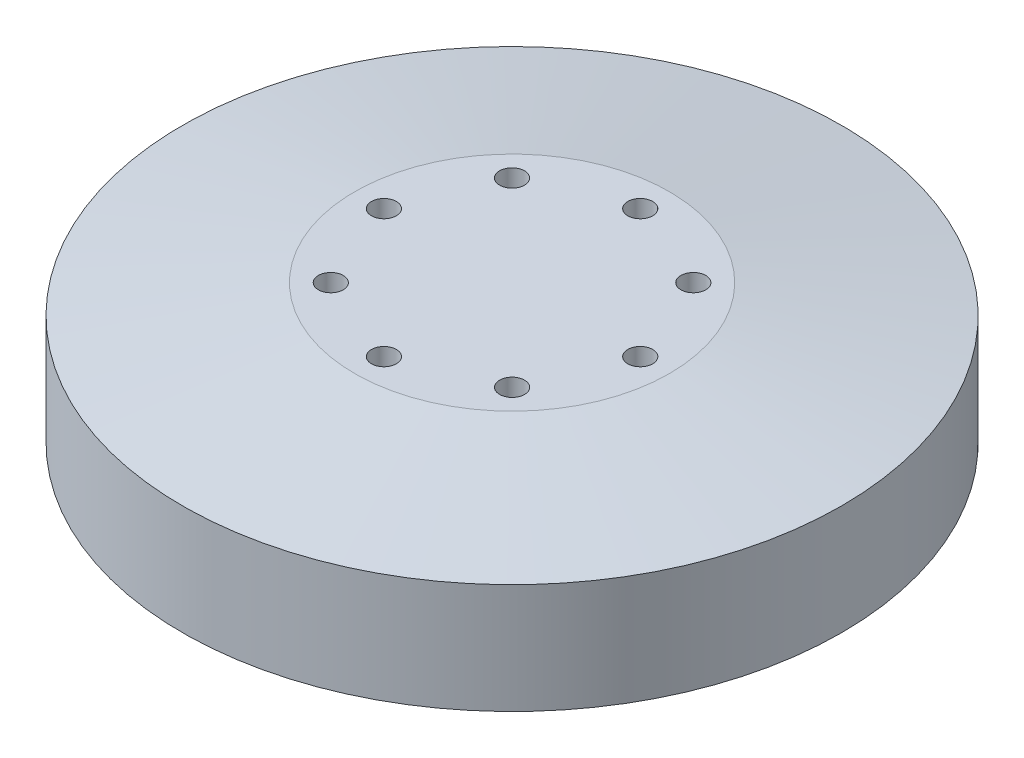
SolidWorks part; units mm, degrees
ref_plane "Front Plane" through (0, 0, 0) normal (0, 0, 1) x (1, 0, 0)
ref_plane "Top Plane" through (0, 0, 0) normal (0, 1, 0) x (1, 0, 0)
ref_plane "Right Plane" through (0, 0, 0) normal (1, 0, 0) x (0, 0, -1)
sketch "Sketch1" plane through (0, 0, 0) normal (0, 0, 1) x (1, 0, 0)
  line L0 (0, -9.45) -> (0, 9.45)
  line L1 (0, 9.45) -> (-21.5, 9.45)
  line L2 (-21.5, 9.45) -> (-45, 5.55)
  line L3 (-45, 5.55) -> (-45, -9.45)
  line L4 (-45, -9.45) -> (0, -9.45)
  point P4 (0, 0)
  dimension "D1" = 21.5
  dimension "D2" = 45
  dimension "D3" = 3.9
  dimension "D4" = 18.9
revolve "Revolve1" add sketch "Sketch1" angle 360 about L0
sketch "Sketch2" plane through (0, -9.45, 0) normal (0, -1, 0) x (1, 0, 0)
  circle A2 centre (0, 0) radius 43
  circle A3 centre (0, 0) radius 43
  dimension "D1" = 2
extrude "Cut-Extrude1" cut sketch "Sketch2" against normal blind 1
sketch "Sketch5" plane through (0, 9.45, 0) normal (0, 1, 0) x (1, 0, 0)
  line L0 (0, -17.5) -> (0, 17.5) construction
  line L1 (17.5, 0) -> (-17.5, 0) construction
  line L2 (12.3744, -12.3744) -> (-12.3744, 12.3744) construction
  line L3 (-12.3744, -12.3744) -> (12.3744, 12.3744) construction
  circle A0 centre (0, 0) radius 17.5 construction
  point P5 (0, 0)
  point P8 (0, 0)
  point P11 (0, 0)
  point P14 (0, 0)
  dimension "D1" = 35
  dimension "D2" = 45
hole_wizard "M3 Clearance Hole1" positions "Sketch6" profile "Sketch7" hole size "M3" standard "ANSI Metric"
sketch "Sketch6" plane through (0, 9.45, 0) normal (0, 1, 0) x (1, 0, 0)
  point P0 (0, 17.5)
  point P3 (-12.3744, 12.3744)
  point P6 (-17.5, 0)
  point P9 (-12.3744, -12.3744)
  point P12 (0, -17.5)
  point P15 (12.3744, -12.3744)
  point P18 (17.5, 0)
  point P21 (12.3744, 12.3744)
sketch "Sketch7" plane through (0, 9.45, -17.5) normal (1, 0, 0) x (0, 0, 1)
  line L0 (0, 0) -> (0, 5.0215)
  line L1 (0, 5.0215) -> (1.7, 4)
  line L2 (1.7, 4) -> (1.7, 0)
  line L5 (1.7, 0) -> (0, 0)
  line L10 (0, 5.0215) -> (-1.7, 4) construction
  line L11 (0, -6.35) -> (0, 107.95) construction
  dimension "Hole Dia." = 3.4
  dimension "Hole Depth" = 4
  dimension "Drill Angle" = 118
